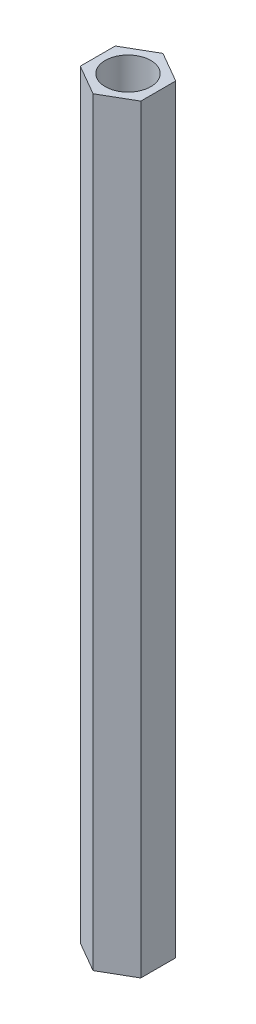
SolidWorks part; units mm, degrees
material "黄铜"
ref_plane "前视基准面" through (0, 0, 0) normal (0, 0, 1) x (1, 0, 0)
ref_plane "上视基准面" through (0, 0, 0) normal (0, 1, 0) x (1, 0, 0)
ref_plane "右视基准面" through (0, 0, 0) normal (1, 0, 0) x (0, 0, -1)
other "Configuration Table"
sketch "草图1" plane through (0, 0, 0) normal (0, 1, 0) x (1, 0, 0)
  line L0 (0, 0) -> (0, 5.7011) construction
  line L1 (0, 2.3) -> (-1.9919, 1.15)
  line L2 (-1.9919, 1.15) -> (-1.9919, -1.15)
  line L3 (-1.9919, -1.15) -> (0, -2.3)
  line L4 (0, -2.3) -> (1.9919, -1.15)
  line L5 (1.9919, -1.15) -> (1.9919, 1.15)
  line L6 (1.9919, 1.15) -> (0, 2.3)
  circle A0 centre (0, 0) radius 1.5
  circle A1 centre (0, 0) radius 1.9919 construction
  dimension "D1" = 3
  dimension "D2" = 4.6
extrude "凸台-拉伸1" add sketch "草图1" along normal blind 50
